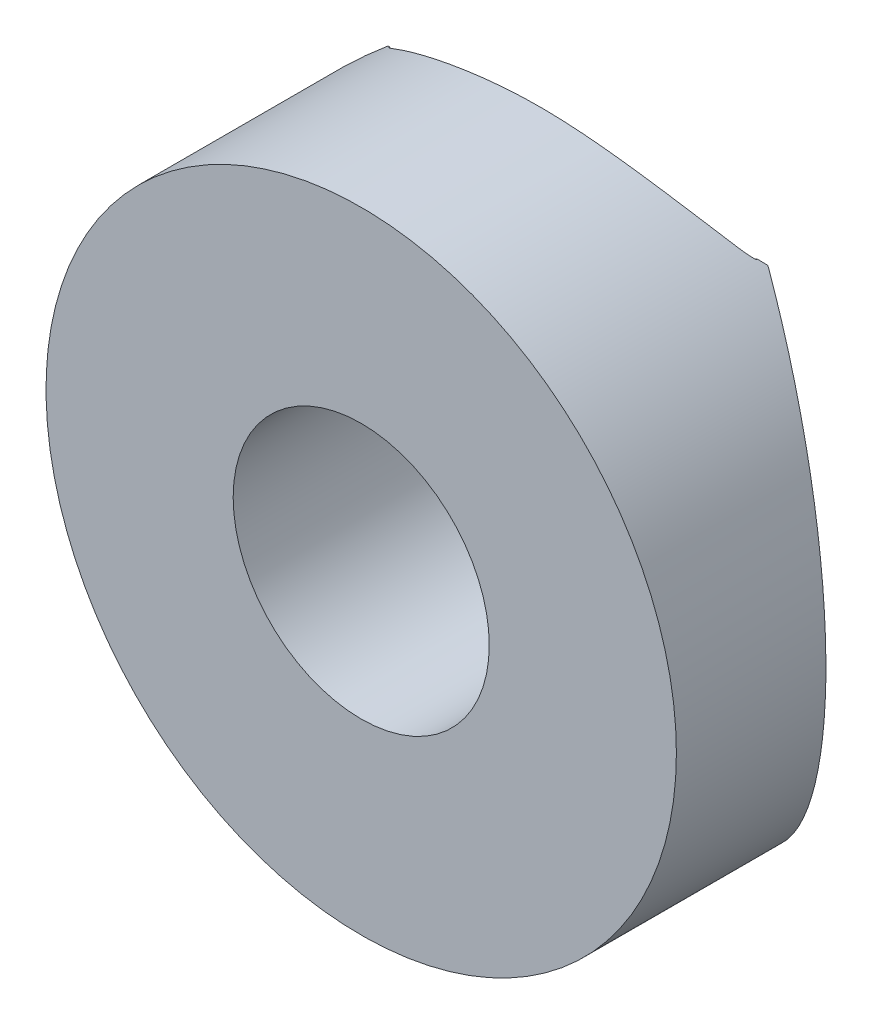
SolidWorks part; units mm, degrees
ref_plane "Alzado" through (0, 0, 0) normal (0, 0, 1) x (1, 0, 0)
ref_plane "Planta" through (0, 0, 0) normal (0, 1, 0) x (1, 0, 0)
ref_plane "Vista lateral" through (0, 0, 0) normal (1, 0, 0) x (0, 0, -1)
sketch "Croquis1" plane through (0, 0, 0) normal (0, 0, 1) x (1, 0, 0)
  circle A0 centre (0, 0) radius 8
  circle A1 centre (0, 0) radius 3.25
  dimension "D1" = 16
  dimension "D2" = 6.5
extrude "Saliente-Extruir1" add sketch "Croquis1" along normal blind 5.5
ref_plane "Plano1" through (0, 6.5, 0) normal (0, 1, 0) x (1, 0, 0)
sketch "Croquis3" plane through (0, 6.5, 0) normal (0, 1, 0) x (1, 0, 0)
  line L0 (0, 0) -> (0, 8.2863) construction
  circle A0 centre (0, 6.6321) radius 8.2
  dimension "D1" = 16.4
extrude "Cortar-Extruir1" cut sketch "Croquis3" against normal blind 3.2 and the other way blind 0.2
sketch "Croquis4" plane through (0, 6.5, 0) normal (0, 1, 0) x (1, 0, 0)
  line L1 (-4.8223, 1.5471) -> (4.8223, 1.5471)
  spline S0 degree 3 poles (-4.3715, -0.3054) (-2.9611, -0.9091) (-0.0366, -1.1567) (3.0343, -0.8778) (4.3715, -0.3054) knots 0 0 0 0 0.5 1 1 1 1
  spline S1 degree 3 poles (-4.3715, -0.3054) (-5.099, 0.0059) (-5.2493, 0.6234) (-4.8223, 1.5471) knots 0 0 0 0 1 1 1 1
  spline S2 degree 3 poles (4.3715, -0.3054) (5.099, 0.0059) (5.2493, 0.6234) (4.8223, 1.5471) knots 0 0 0 0 1 1 1 1
extrude "Cortar-Extruir2" cut sketch "Croquis4" along normal blind 3.4
mirror "Simetría1" about plane through (0, 0, 0) normal (0, 1, 0) of "Cortar-Extruir1", "Cortar-Extruir2"
sketch "Croquis5" plane through (0, 3.3, 0) normal (0, 1, 0) x (1, 0, 0)
  circle A0 centre (0, 8.105) radius 9
  dimension "D1" = 18
extrude "Cortar-Extruir3" cut sketch "Croquis5" against normal up to surface (6.6 mm away) up to face at (0, -3.3, 0.7839)
sketch "Croquis6" plane through (0, 0, 0) normal (0, 1, 0) x (1, 0, 0)
  line L0 (-4.8223, 0) -> (-8.4821, -1.964)
  line L1 (-8.4821, -1.964) -> (-8.4821, 2.8689)
  line L2 (-8.4821, 2.8689) -> (8.4821, 2.8689)
  line L3 (0, 0) -> (0, 3.8948) construction
  line L4 (4.8223, 0) -> (8.4821, -1.964)
  line L5 (8.4821, -1.964) -> (8.4821, 2.8689)
  line L6 (-4.8223, 0) -> (-4.8223, 1.2503)
  line L7 (-4.8223, 1.2503) -> (4.8223, 1.2503)
  line L8 (4.8223, 1.2503) -> (4.8223, 0)
  point P11 (0, 2.8689)
extrude "Cortar-Extruir4" cut sketch "Croquis6" against normal through all and the other way through all
